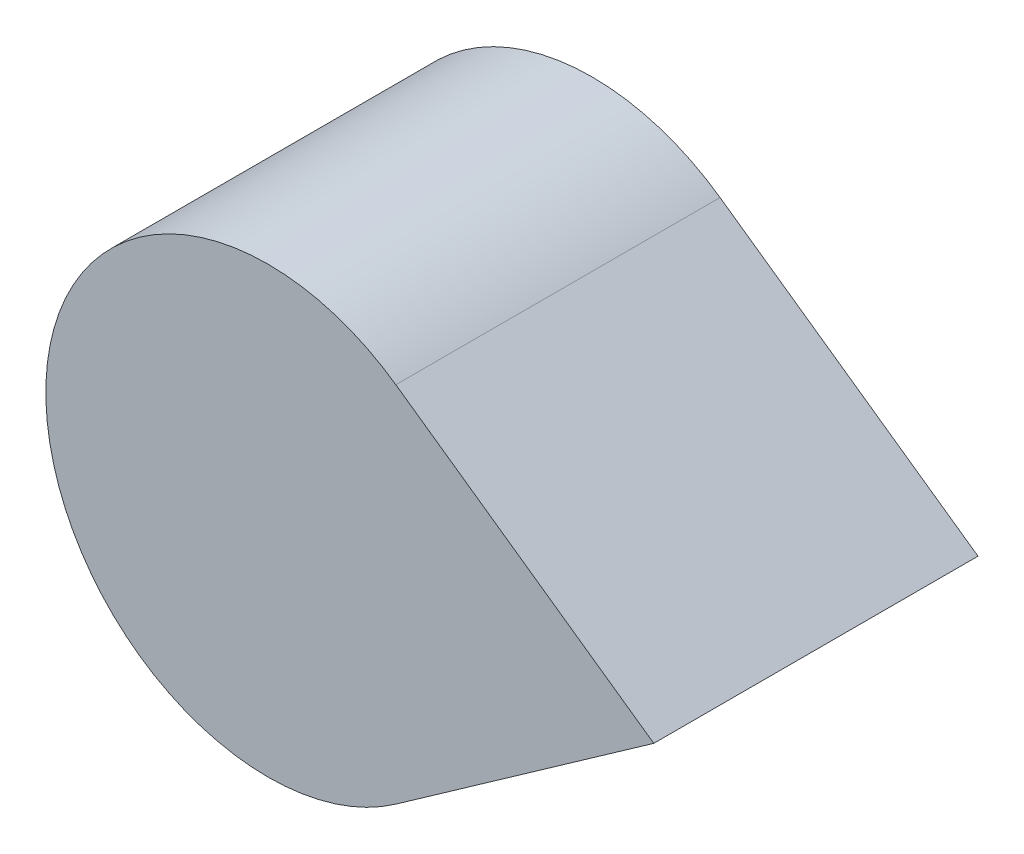
SolidWorks part; units mm, degrees
ref_plane "Front Plane" through (0, 0, 0) normal (0, 0, 1) x (1, 0, 0)
ref_plane "Top Plane" through (0, 0, 0) normal (0, 1, 0) x (1, 0, 0)
ref_plane "Right Plane" through (0, 0, 0) normal (1, 0, 0) x (0, 0, -1)
sketch "Sketch1" plane through (0, 0, 0) normal (0, 0, 1) x (1, 0, 0)
  line L0 (26.6978, 2.9017) -> (22.0822, 5.8511)
  line L1 (26.6978, 2.9017) -> (22.0822, -0.0475)
  line L2 (21.9725, 5.4226) -> (25.5528, 2.9017)
  line L3 (25.5528, 2.9017) -> (21.9724, 0.3809)
  circle A0 centre (20.1976, 2.9018) radius 3.5
  circle A1 centre (20.1976, 2.9018) radius 3.083
extrude "Boss-Extrude1" add sketch "Sketch1" against normal blind 4.5 contours A1 | A0 L3 L2 | A1 L3 A0 L2
